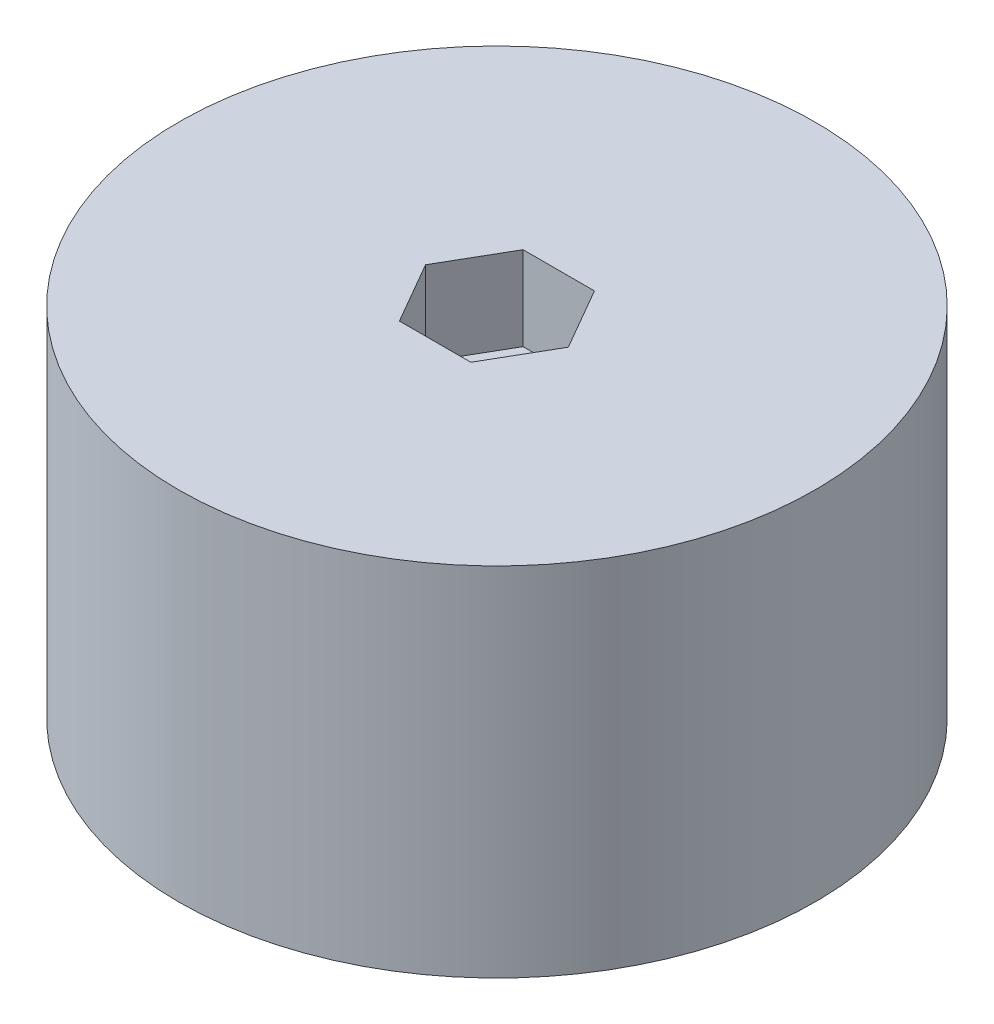
SolidWorks part; units mm, degrees
ref_plane "Front Plane" through (0, 0, 0) normal (0, 0, 1) x (1, 0, 0)
ref_plane "Top Plane" through (0, 0, 0) normal (0, 1, 0) x (1, 0, 0)
ref_plane "Right Plane" through (0, 0, 0) normal (1, 0, 0) x (0, 0, -1)
sketch "Sketch1" plane through (0, 0, 0) normal (0, 1, 0) x (1, 0, 0)
  circle A0 centre (0, 0) radius 22.75
  circle A1 centre (0, 0) radius 3
  dimension "D1" = 45.5
  dimension "D2" = 6
extrude "Boss-Extrude1" add sketch "Sketch1" along normal blind 25.5
sketch "Sketch2" plane through (0, 25.5, 0) normal (0, 1, 0) x (1, 0, 0)
  line L1 (5.1, 0) -> (2.55, 4.4167)
  line L2 (2.55, 4.4167) -> (-2.55, 4.4167)
  line L3 (-2.55, 4.4167) -> (-5.1, 0)
  line L4 (-5.1, 0) -> (-2.55, -4.4167)
  line L5 (-2.55, -4.4167) -> (2.55, -4.4167)
  line L6 (2.55, -4.4167) -> (5.1, 0)
  circle A0 centre (0, 0) radius 4.4167 construction
  dimension "D1" = 5.1
extrude "Cut-Extrude1" cut sketch "Sketch2" against normal blind 6
